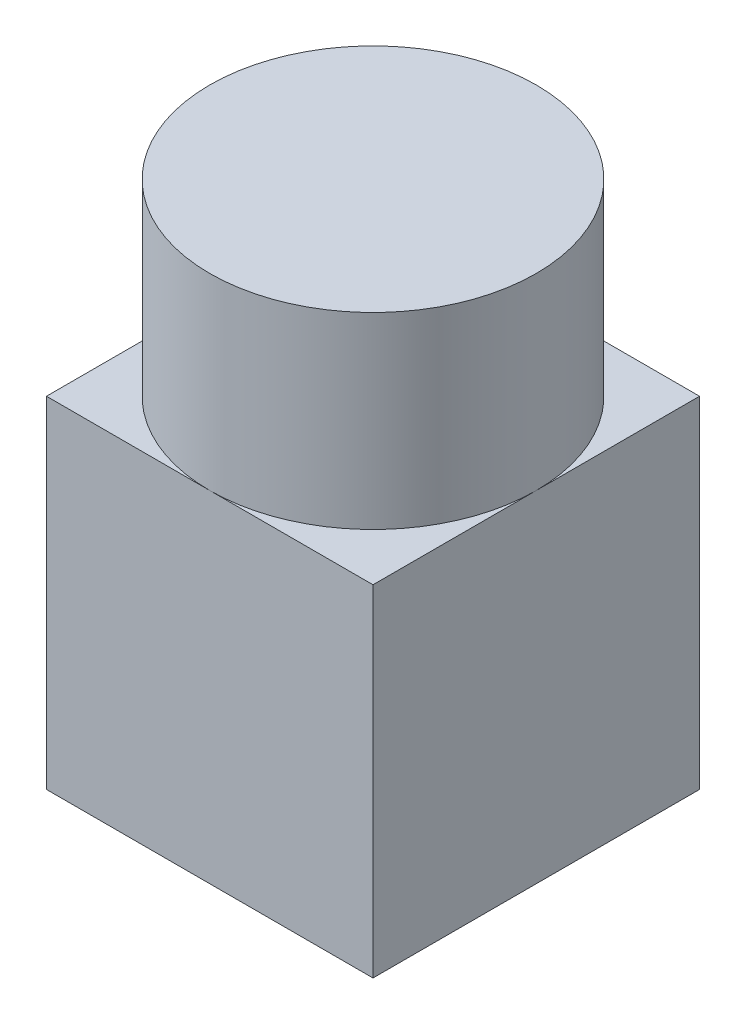
SolidWorks part; units mm, degrees
ref_plane "Front Plane" through (0, 0, 0) normal (0, 0, 1) x (1, 0, 0)
ref_plane "Top Plane" through (0, 0, 0) normal (0, 1, 0) x (1, 0, 0)
ref_plane "Right Plane" through (0, 0, 0) normal (1, 0, 0) x (0, 0, -1)
sketch "Sketch1" plane through (0, 0, 0) normal (0, 1, 0) x (1, 0, 0)
  line L1 (-14.55, 14.55) -> (14.55, 14.55)
  line L2 (-14.55, 14.55) -> (-14.55, -14.55)
  line L3 (-14.55, -14.55) -> (14.55, -14.55)
  line L4 (14.55, 14.55) -> (14.55, -14.55)
  line L5 (-14.55, 14.55) -> (14.55, -14.55) construction
  line L6 (-14.55, -14.55) -> (14.55, 14.55) construction
  point P0 (0, 0)
  dimension "D1" = 29.1
extrude "Boss-Extrude1" add sketch "Sketch1" along normal blind 30.35
sketch "Sketch2" plane through (0, 30.35, 0) normal (0, 1, 0) x (1, 0, 0)
  line L0 (-14.55, 14.55) -> (-14.55, -14.55) construction
  circle A0 centre (0, 0) radius 14.55
extrude "Boss-Extrude2" add sketch "Sketch2" along normal blind 16.75
